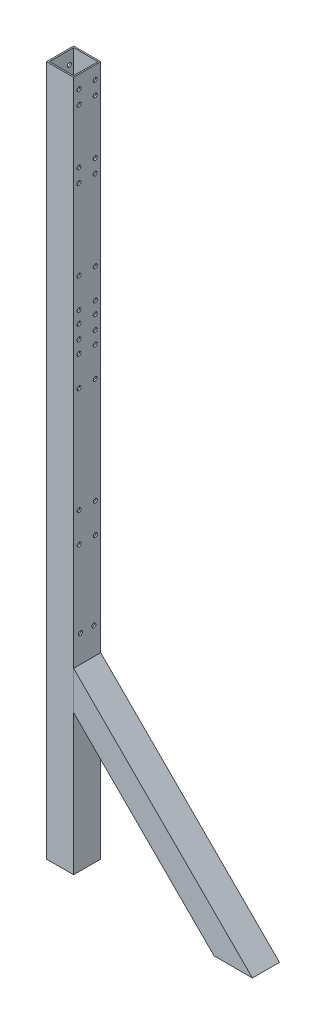
SolidWorks part; units mm, degrees
material "6061 合金"
ref_plane "前视基准面" through (0, 0, 0) normal (0, 0, 1) x (1, 0, 0)
ref_plane "上视基准面" through (0, 0, 0) normal (0, 1, 0) x (1, 0, 0)
ref_plane "右视基准面" through (0, 0, 0) normal (1, 0, 0) x (0, 0, -1)
sketch3d "3D草图1"
  line L0 (0, 0, 0) -> (0, 520, 0)
  line L1 (0, 137.8858, 0) -> (137.8858, 0, 0)
  line L2 (0, 0, 0) -> (100, 0, 0)
  dimension "D1" = 520
  dimension "D2" = 45
  dimension "D3" = 195
  dimension "D4" = 100
other "Hs 20X20X1(1)"
ref_plane "基准面2" through (0, 0, 0) normal (0, 1, 0) x (1, 0, 0)
sketch "草图1" plane through (0, 0, 0) normal (0, 1, 0) x (1, 0, 0)
  line L0 (-9, -9) -> (-9, 9)
  line L1 (-10, -10) -> (10, -10)
  line L2 (-10, -10) -> (-10, 10)
  line L3 (-10, 10) -> (10, 10)
  line L4 (10, -10) -> (10, 10)
  line L5 (-10, -10) -> (10, 10) construction
  line L6 (-10, 10) -> (10, -10) construction
  line L7 (-9, 9) -> (9, 9)
  line L8 (9, -9) -> (9, 9)
  line L9 (-9, -9) -> (9, -9)
  point P0 (0, 0)
  point P10 (0, 0)
  dimension "D1" = 1
sketch "草图2" plane through (0, 0, 10) normal (0, 0, 1) x (1, 0, 0)
  line L0 (-10, 520) -> (-10, -10) construction
  line L1 (100, -10) -> (-10, -10)
  line L2 (100, -10) -> (100, 10)
  line L3 (100, 10) -> (-10, 10)
  line L4 (-10, -10) -> (-10, 10)
  line L5 (100, 10) -> (10, 10) construction
extrude "切除-拉伸1" cut sketch "草图2" against normal blind 41
sketch "草图5" plane through (10, 0, 0) normal (1, 0, 0) x (0, 0, -1)
  circle A0 centre (5, 162) radius 1.5
  circle A2 centre (-5, 162) radius 1.5
  dimension "D1" = 3
  dimension "D2" = 3
extrude "切除-拉伸3" cut sketch "草图5" against normal blind 41
sketch "草图6" plane through (10, 0, 0) normal (1, 0, 0) x (0, 0, -1)
  circle A0 centre (-6, 369.1719) radius 1.5
  circle A1 centre (6, 369.1719) radius 1.5
  circle A2 centre (-6, 391.1719) radius 1.5
  circle A3 centre (6, 391.1719) radius 1.5
  circle A4 centre (-6.05, 510.4219) radius 1.5
  circle A5 centre (-6.05, 500.4219) radius 1.5
  circle A6 centre (5.95, 500.4219) radius 1.5
  circle A7 centre (5.95, 510.4219) radius 1.5
  dimension "D1" = 3
  dimension "D2" = 3
  dimension "D3" = 3
  dimension "D4" = 3
  dimension "D5" = 3
  dimension "D6" = 3
  dimension "D7" = 3
  dimension "D8" = 3
extrude "切除-拉伸4" cut sketch "草图6" against normal blind 31
sketch "草图7" plane through (0, 0, 10) normal (0, 0, 1) x (1, 0, 0)
  line L1 (-10, 10) -> (195.4071, 10)
  line L2 (-10, 10) -> (-10, -27.6483)
  line L3 (-10, -27.6483) -> (195.4071, -27.6483)
  line L4 (195.4071, 10) -> (195.4071, -27.6483)
extrude "切除-拉伸5" cut sketch "草图7" against normal through all
sketch "草图8" plane through (10, 0, 0) normal (1, 0, 0) x (0, 0, -1)
  line L0 (0, 520) -> (0, 142.028) construction
  line L1 (-10, 520) -> (10, 520) construction
  line L2 (-10, 142.028) -> (10, 142.028) construction
  line L3 (-0.0818, 620) -> (-0.0818, 242.0279) construction
  circle A0 centre (6, 369.1719) radius 1.5 construction
  circle A1 centre (-6, 369.1719) radius 1.5 construction
  circle A2 centre (6, 391.1719) radius 1.5 construction
  circle A3 centre (-6, 391.1719) radius 1.5 construction
  circle A4 centre (5.95, 500.4219) radius 1.5 construction
  circle A5 centre (-6.05, 500.4219) radius 1.5 construction
  circle A6 centre (5.95, 510.4219) radius 1.5 construction
  circle A7 centre (-6.05, 510.4219) radius 1.5 construction
  circle A8 centre (6, 369.1719) radius 1.5 construction
  circle A9 centre (-6, 369.1719) radius 1.5 construction
  circle A10 centre (6, 391.1719) radius 1.5 construction
  circle A11 centre (-6, 391.1719) radius 1.5 construction
  circle A12 centre (5.95, 500.4219) radius 1.5 construction
  circle A13 centre (-6.05, 500.4219) radius 1.5 construction
  circle A14 centre (5.95, 510.4219) radius 1.5 construction
  circle A15 centre (-6.05, 510.4219) radius 1.5 construction
  circle A16 centre (6.0372, 219.1719) radius 1.5
  circle A17 centre (-5.9628, 219.1719) radius 1.5
  circle A18 centre (6.0372, 241.1719) radius 1.5
  circle A19 centre (-5.9628, 241.1719) radius 1.5
  circle A20 centre (5.9872, 350.4219) radius 1.5
  circle A21 centre (-6.0128, 350.4219) radius 1.5
  circle A22 centre (5.9872, 360.4219) radius 1.5
  circle A23 centre (-6.0128, 360.4219) radius 1.5
  circle A24 centre (5.9554, 319.1719) radius 1.5
  circle A25 centre (-6.0446, 319.1719) radius 1.5
  circle A26 centre (5.9554, 341.1719) radius 1.5
  circle A27 centre (-6.0446, 341.1719) radius 1.5
  circle A28 centre (5.9054, 450.4219) radius 1.5
  circle A29 centre (-6.0946, 450.4219) radius 1.5
  circle A30 centre (5.9054, 460.4219) radius 1.5
  circle A31 centre (-6.0946, 460.4219) radius 1.5
  dimension "D1" = 2
  dimension "D2" = 2
extrude "切除-拉伸6" cut sketch "草图8" against normal through all
sketch "草图9" plane through (-10, 0, 0) normal (-1, 0, 0) x (0, 0, 1)
  line L4 (-10, 520) -> (-10, 10)
  line L5 (-10, 10) -> (10, 10)
  line L6 (10, 10) -> (10, 520)
  line L7 (10, 520) -> (-10, 520)
  line L8 (-10, 520) -> (-10, 10)
  line L9 (-10, 10) -> (10, 10)
  line L10 (10, 10) -> (10, 520)
  line L11 (10, 520) -> (-10, 520)
  circle A0 centre (5, 162) radius 1.5 construction
  circle A1 centre (-5, 162) radius 1.5 construction
  circle A2 centre (5.9628, 219.1719) radius 1.5 construction
  circle A3 centre (-6.0372, 219.1719) radius 1.5 construction
  circle A4 centre (5.9628, 241.1719) radius 1.5 construction
  circle A5 centre (-6.0372, 241.1719) radius 1.5 construction
  circle A6 centre (6.0446, 319.1719) radius 1.5 construction
  circle A7 centre (-5.9554, 319.1719) radius 1.5 construction
  circle A8 centre (6.0446, 341.1719) radius 1.5 construction
  circle A9 centre (-5.9554, 341.1719) radius 1.5 construction
  circle A10 centre (6.0128, 350.4219) radius 1.5 construction
  circle A11 centre (-5.9872, 350.4219) radius 1.5 construction
  circle A12 centre (6.0128, 360.4219) radius 1.5 construction
  circle A13 centre (-5.9872, 360.4219) radius 1.5 construction
  circle A14 centre (6, 369.1719) radius 1.5 construction
  circle A15 centre (-6, 369.1719) radius 1.5 construction
  circle A16 centre (6, 391.1719) radius 1.5 construction
  circle A17 centre (-6, 391.1719) radius 1.5 construction
  circle A18 centre (6.0946, 450.4219) radius 1.5 construction
  circle A19 centre (-5.9054, 450.4219) radius 1.5 construction
  circle A20 centre (6.0946, 460.4219) radius 1.5 construction
  circle A21 centre (-5.9054, 460.4219) radius 1.5 construction
  circle A22 centre (6.05, 500.4219) radius 1.5 construction
  circle A23 centre (-5.95, 500.4219) radius 1.5 construction
  circle A24 centre (6.05, 510.4219) radius 1.5 construction
  circle A25 centre (-5.95, 510.4219) radius 1.5 construction
  circle A26 centre (5, 162) radius 1.5
  circle A27 centre (-5, 162) radius 1.5
  circle A28 centre (5.9628, 219.1719) radius 1.5
  circle A29 centre (-6.0372, 219.1719) radius 1.5
  circle A30 centre (5.9628, 241.1719) radius 1.5
  circle A31 centre (-6.0372, 241.1719) radius 1.5
  circle A32 centre (6.0446, 319.1719) radius 1.5
  circle A33 centre (-5.9554, 319.1719) radius 1.5
  circle A34 centre (6.0446, 341.1719) radius 1.5
  circle A35 centre (-5.9554, 341.1719) radius 1.5
  circle A36 centre (6.0128, 350.4219) radius 1.5
  circle A37 centre (-5.9872, 350.4219) radius 1.5
  circle A38 centre (6.0128, 360.4219) radius 1.5
  circle A39 centre (-5.9872, 360.4219) radius 1.5
  circle A40 centre (6, 369.1719) radius 1.5
  circle A41 centre (-6, 369.1719) radius 1.5
  circle A42 centre (6, 391.1719) radius 1.5
  circle A43 centre (-6, 391.1719) radius 1.5
  circle A44 centre (6.0946, 450.4219) radius 1.5
  circle A45 centre (-5.9054, 450.4219) radius 1.5
  circle A46 centre (6.0946, 460.4219) radius 1.5
  circle A47 centre (-5.9054, 460.4219) radius 1.5
  circle A48 centre (6.05, 500.4219) radius 1.5
  circle A49 centre (-5.95, 500.4219) radius 1.5
  circle A50 centre (6.05, 510.4219) radius 1.5
  circle A51 centre (-5.95, 510.4219) radius 1.5
  dimension "D1" = 0
